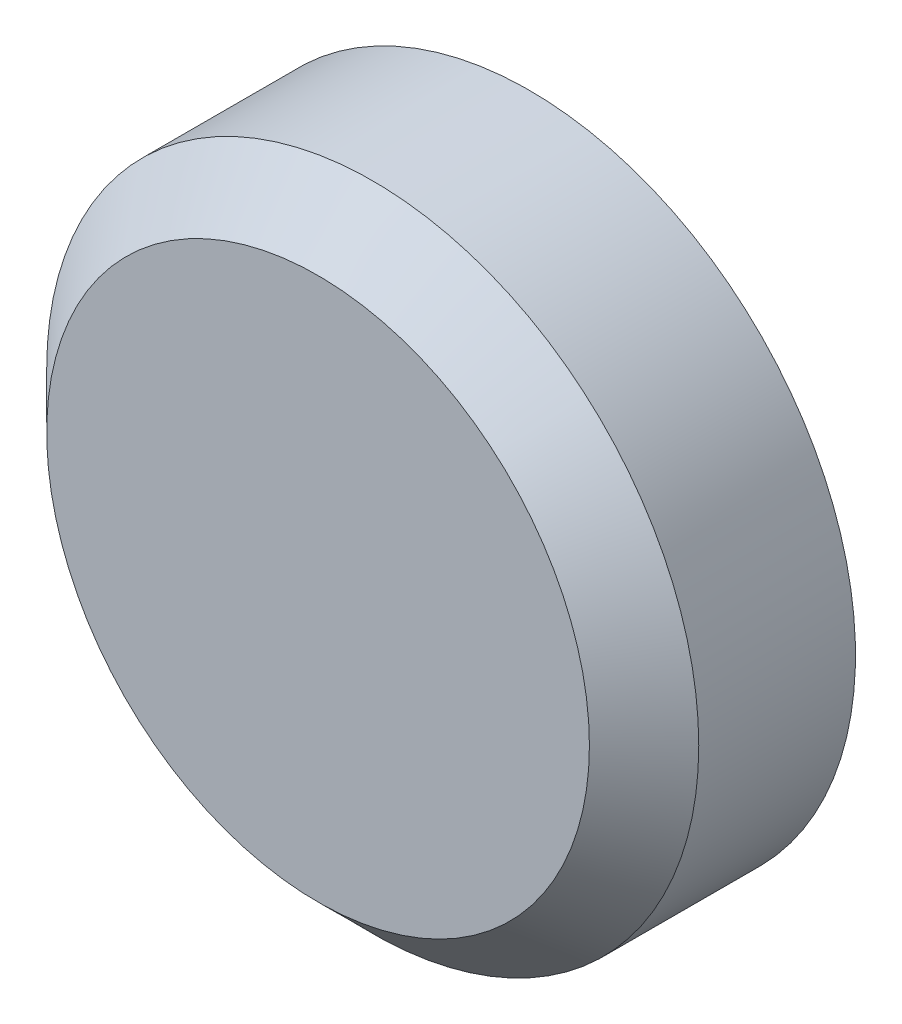
SolidWorks part; units mm, degrees
ref_plane "Front Plane" through (0, 0, 0) normal (0, 0, 1) x (1, 0, 0)
ref_plane "Top Plane" through (0, 0, 0) normal (0, 1, 0) x (1, 0, 0)
ref_plane "Right Plane" through (0, 0, 0) normal (1, 0, 0) x (0, 0, -1)
sketch "Sketch1" plane through (0, 0, 0) normal (0, 0, 1) x (1, 0, 0)
  circle A0 centre (0, 0) radius 76.75
  circle A1 centre (0, 0) radius 89.45
  dimension "D1" = 153.5
  dimension "D2" = 178.9
extrude "Boss-Extrude1" add sketch "Sketch1" along normal blind 33
sketch "Sketch2" plane through (0, 0, 0) normal (0, 0, -1) x (-1, 0, 0)
  circle A0 centre (0, 0) radius 89.45
  circle A1 centre (0, 0) radius 85
  circle A2 centre (0, 0) radius 89.45 construction
  dimension "D2" = 170
extrude "Boss-Extrude2" add sketch "Sketch2" along normal blind 5
sketch "Sketch3" plane through (0, 0, 33) normal (0, 0, 1) x (1, 0, 0)
  circle A0 centre (0, 0) radius 89.45
  circle A1 centre (0, 0) radius 89.45 construction
extrude "Boss-Extrude3" add sketch "Sketch3" along normal blind 20
chamfer "Chamfer1" distance 15 angle 45 1 edges at (89.45, 0, 53)
chamfer "Chamfer2" distance 5 angle 20 1 edges at (76.75, 0, 0)
fillet "Fillet1" radius 10 1 edges at (76.75, 0, 5)
fillet "Fillet2" radius 2 1 edges at (78.5699, 0, 0)
fillet "Fillet3" radius 5 1 edges at (76.75, 0, 33)
